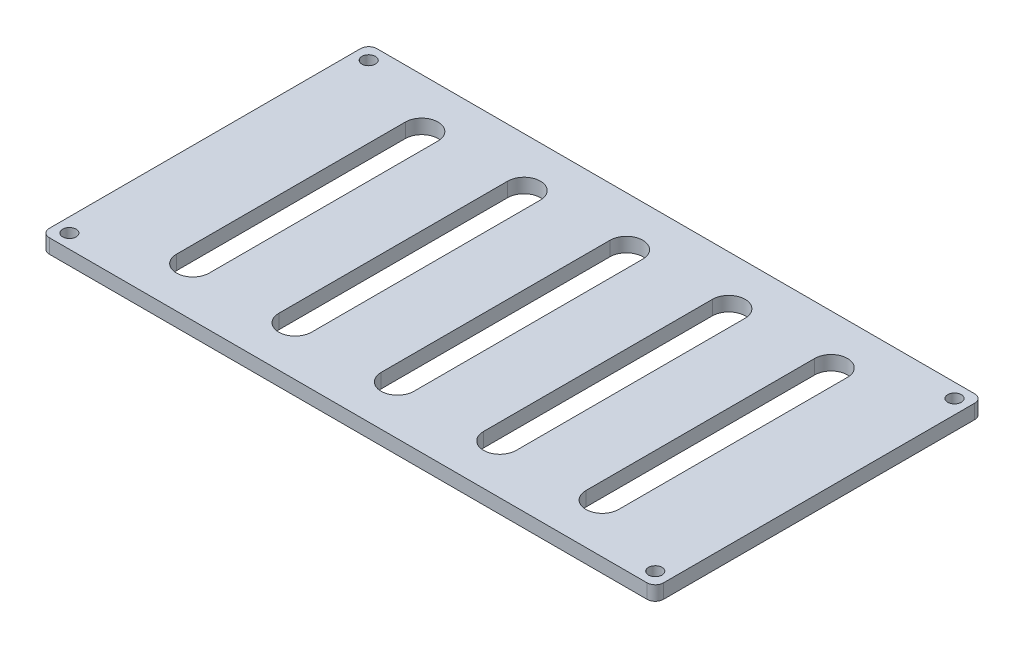
SolidWorks part; units mm, degrees
ref_plane "Front Plane" through (0, 0, 0) normal (0, 0, 1) x (1, 0, 0)
ref_plane "Top Plane" through (0, 0, 0) normal (0, 1, 0) x (1, 0, 0)
ref_plane "Right Plane" through (0, 0, 0) normal (1, 0, 0) x (0, 0, -1)
sketch "Sketch1" plane through (0, 0, 0) normal (0, 1, 0) x (1, 0, 0)
  line L1 (-73, -40) -> (73, -40)
  line L2 (-75, -38) -> (-75, 38)
  line L3 (-73, 40) -> (73, 40)
  line L4 (75, -38) -> (75, 38)
  line L5 (-75, -40) -> (75, 40) construction
  line L6 (-75, 40) -> (75, -40) construction
  line L10 (-71.5, -0.0048) -> (71.5, -0.0048) construction
  line L11 (-74.4142, 39.4142) -> (-68.6716, 33.6716) construction
  line L12 (0, 40) -> (0, -40) construction
  line L13 (0, -27.9576) -> (0, 27.9481) construction
  line L14 (-4, -27.9576) -> (-4, 27.9481)
  line L15 (4, -27.9576) -> (4, 27.9481)
  line L16 (29, -27.9576) -> (29, 27.9481)
  line L17 (21, -27.9576) -> (21, 27.9481)
  line L18 (25, -27.9576) -> (25, 27.9481) construction
  line L19 (54, -27.9576) -> (54, 27.9481)
  line L20 (46, -27.9576) -> (46, 27.9481)
  line L21 (50, -27.9576) -> (50, 27.9481) construction
  line L22 (4, -27.9576) -> (4, 27.9481)
  line L23 (-4, -27.9576) -> (-4, 27.9481)
  line L24 (0, -27.9576) -> (0, 27.9481) construction
  line L25 (29, -27.9576) -> (29, 27.9481)
  line L26 (21, -27.9576) -> (21, 27.9481)
  line L27 (25, -27.9576) -> (25, 27.9481) construction
  line L28 (-21, -27.9576) -> (-21, 27.9481)
  line L29 (-29, -27.9576) -> (-29, 27.9481)
  line L30 (-25, -27.9576) -> (-25, 27.9481) construction
  line L31 (4, -27.9576) -> (4, 27.9481)
  line L32 (-4, -27.9576) -> (-4, 27.9481)
  line L33 (0, -27.9576) -> (0, 27.9481) construction
  line L34 (-21, -27.9576) -> (-21, 27.9481)
  line L35 (-29, -27.9576) -> (-29, 27.9481)
  line L36 (-25, -27.9576) -> (-25, 27.9481) construction
  line L37 (-46, -27.9576) -> (-46, 27.9481)
  line L38 (-54, -27.9576) -> (-54, 27.9481)
  line L39 (-50, -27.9576) -> (-50, 27.9481) construction
  arc A0 (73, 40) -> (75, 38) centre (73, 38) cw
  arc A1 (75, -38) -> (73, -40) centre (73, -38) cw
  arc A2 (-73, -40) -> (-75, -38) centre (-73, -38) cw
  arc A3 (-75, 38) -> (-73, 40) centre (-73, 38) cw
  circle A4 centre (-71.5429, 36.5429) radius 1.65
  circle A5 centre (71.5429, 36.5429) radius 1.65
  circle A6 centre (71.5429, -36.5524) radius 1.65
  circle A7 centre (-71.5429, -36.5524) radius 1.65
  arc A8 (-4, -27.9576) -> (4, -27.9576) centre (0, -27.9576) ccw
  arc A9 (4, 27.9481) -> (-4, 27.9481) centre (0, 27.9481) ccw
  arc A10 (21, -27.9576) -> (29, -27.9576) centre (25, -27.9576) ccw
  arc A11 (29, 27.9481) -> (21, 27.9481) centre (25, 27.9481) ccw
  arc A12 (46, -27.9576) -> (54, -27.9576) centre (50, -27.9576) ccw
  arc A13 (54, 27.9481) -> (46, 27.9481) centre (50, 27.9481) ccw
  arc A14 (-4, -27.9576) -> (4, -27.9576) centre (0, -27.9576) ccw
  arc A15 (4, 27.9481) -> (-4, 27.9481) centre (0, 27.9481) ccw
  arc A16 (21, -27.9576) -> (29, -27.9576) centre (25, -27.9576) ccw
  arc A17 (29, 27.9481) -> (21, 27.9481) centre (25, 27.9481) ccw
  arc A18 (-29, -27.9576) -> (-21, -27.9576) centre (-25, -27.9576) ccw
  arc A19 (-21, 27.9481) -> (-29, 27.9481) centre (-25, 27.9481) ccw
  arc A20 (-4, -27.9576) -> (4, -27.9576) centre (0, -27.9576) ccw
  arc A21 (4, 27.9481) -> (-4, 27.9481) centre (0, 27.9481) ccw
  arc A22 (-29, -27.9576) -> (-21, -27.9576) centre (-25, -27.9576) ccw
  arc A23 (-21, 27.9481) -> (-29, 27.9481) centre (-25, 27.9481) ccw
  arc A24 (-54, -27.9576) -> (-46, -27.9576) centre (-50, -27.9576) ccw
  arc A25 (-46, 27.9481) -> (-54, 27.9481) centre (-50, 27.9481) ccw
  point P0 (0, 0)
  point P22 (0, 36.5)
  point P25 (0, -0.0048)
  point P36 (0, -0.0048)
  point P46 (25, -0.0048)
  point P53 (50, -0.0048)
  point P60 (0, -0.0048)
  point P67 (25, -0.0048)
  point P74 (-25, -0.0048)
  point P81 (0, -0.0048)
  point P88 (-25, -0.0048)
  point P95 (-50, -0.0048)
  dimension "D3" = 2
  dimension "D4" = 3.3
  dimension "D1" = 150
  dimension "D2" = 80
  dimension "D5" = 8
  dimension "D6" = 0
  dimension "D7" = 3
  dimension "D8" = 3
extrude "Boss-Extrude1" add sketch "Sketch1" along normal blind 3.5 contours A3 L2 A2 L1 A1 L4 A0 L3 A25 L37 A24 L38 A19 L28 A18 L29 A13 L19 A12 L20 A11 L16 A10 L17 A9 L15 A8 L14 A5 A4 A6 A7
